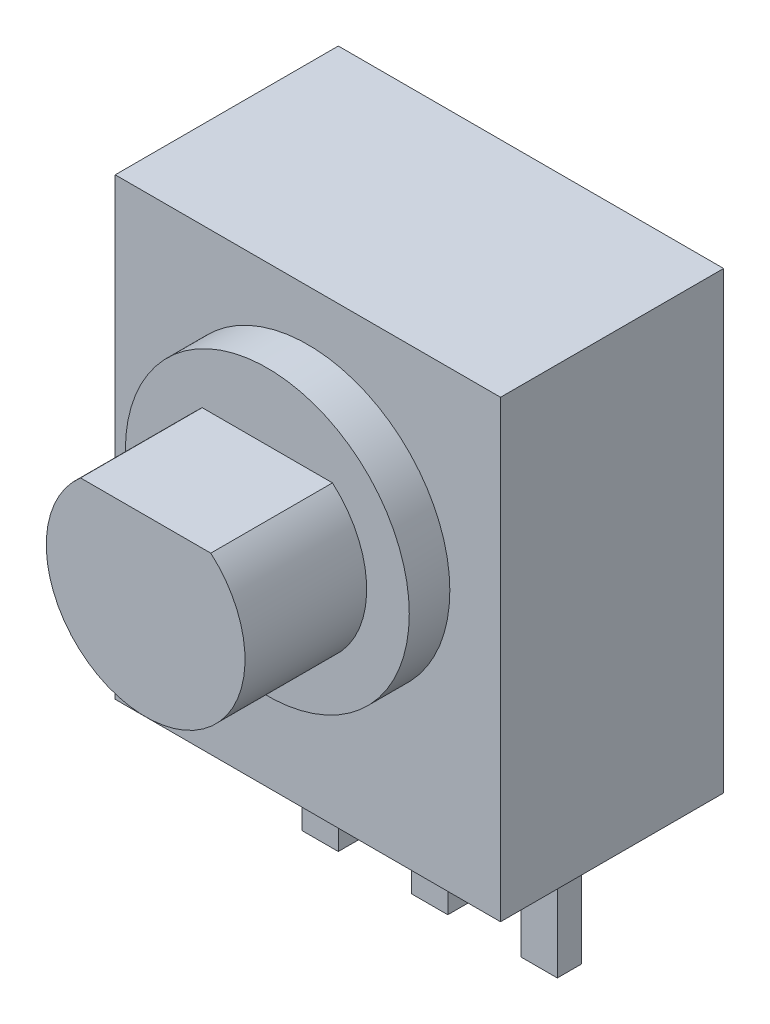
SolidWorks part; units mm, degrees
ref_plane "Front Plane" through (0, 0, 0) normal (0, 0, 1) x (1, 0, 0)
ref_plane "Top Plane" through (0, 0, 0) normal (0, 1, 0) x (1, 0, 0)
ref_plane "Right Plane" through (0, 0, 0) normal (1, 0, 0) x (0, 0, -1)
sketch "Sketch1" plane through (0, 0, 0) normal (0, 0, 1) x (1, 0, 0)
  line L1 (-4.75, -4.75) -> (4.75, -4.75)
  line L2 (-4.75, -4.75) -> (-4.75, 4.75)
  line L3 (-4.75, 4.75) -> (4.75, 4.75)
  line L4 (4.75, -4.75) -> (4.75, 4.75)
  line L5 (-4.75, -4.75) -> (4.75, 4.75) construction
  line L6 (-4.75, 4.75) -> (4.75, -4.75) construction
  point P0 (0, 0)
  dimension "D1" = 9.5
  dimension "D2" = 9.5
extrude "Boss-Extrude1" add sketch "Sketch1" against normal blind 5.5
sketch "Sketch2" plane through (0, -4.75, 0) normal (0, -1, 0) x (1, 0, 0)
  line L1 (-4.75, 0) -> (4.75, 0)
  line L2 (-4.75, 0) -> (-4.75, -5.5)
  line L3 (-4.75, -5.5) -> (4.75, -5.5)
  line L4 (4.75, 0) -> (4.75, -5.5)
extrude "Boss-Extrude2" add sketch "Sketch2" along normal blind 1.7
sketch "Sketch3" plane through (0, 0, 0) normal (0, 0, 1) x (1, 0, 0)
  circle A0 centre (0, 0) radius 3.5
  dimension "D1" = 7
extrude "Boss-Extrude3" add sketch "Sketch3" along normal blind 1
sketch "Sketch4" plane through (0, 0, 1) normal (0, 0, 1) x (1, 0, 0)
  line L0 (-1.6062, 1.85) -> (1.6062, 1.85)
  arc A0 (-1.6062, 1.85) -> (1.6062, 1.85) centre (0, 0) ccw
  dimension "D1" = 4.9
  dimension "D2" = 1.85
extrude "Boss-Extrude4" add sketch "Sketch4" along normal blind 3
sketch "Sketch5" plane through (0, -6.45, 0) normal (0, -1, 0) x (1, 0, 0)
  line L0 (-4.75, -5.5) -> (4.75, -5.5) construction
  line L1 (-3.15, -3.6) -> (-2.25, -3.6)
  line L2 (-3.15, -3.6) -> (-3.15, -3)
  line L3 (-3.15, -3) -> (-2.25, -3)
  line L4 (-2.25, -3.6) -> (-2.25, -3)
  line L5 (-0.45, -3.6) -> (-0.45, -3)
  line L6 (-0.45, -3.6) -> (0.45, -3.6)
  line L7 (0.45, -3.6) -> (0.45, -3)
  line L8 (-0.45, -3) -> (0.45, -3)
  line L9 (2.25, -3.6) -> (2.25, -3)
  line L10 (2.25, -3.6) -> (3.15, -3.6)
  line L11 (3.15, -3.6) -> (3.15, -3)
  line L12 (2.25, -3) -> (3.15, -3)
  line L13 (4.75, 0) -> (-4.75, 0) construction
  point P8 (0, 0)
  point P18 (0, -3)
  dimension "D1" = 2.5
  dimension "D2" = 0.6
  dimension "D3" = 2.5
  dimension "D4" = 0.9
  dimension "D5" = 3
extrude "Boss-Extrude5" add sketch "Sketch5" along normal blind 3.5
